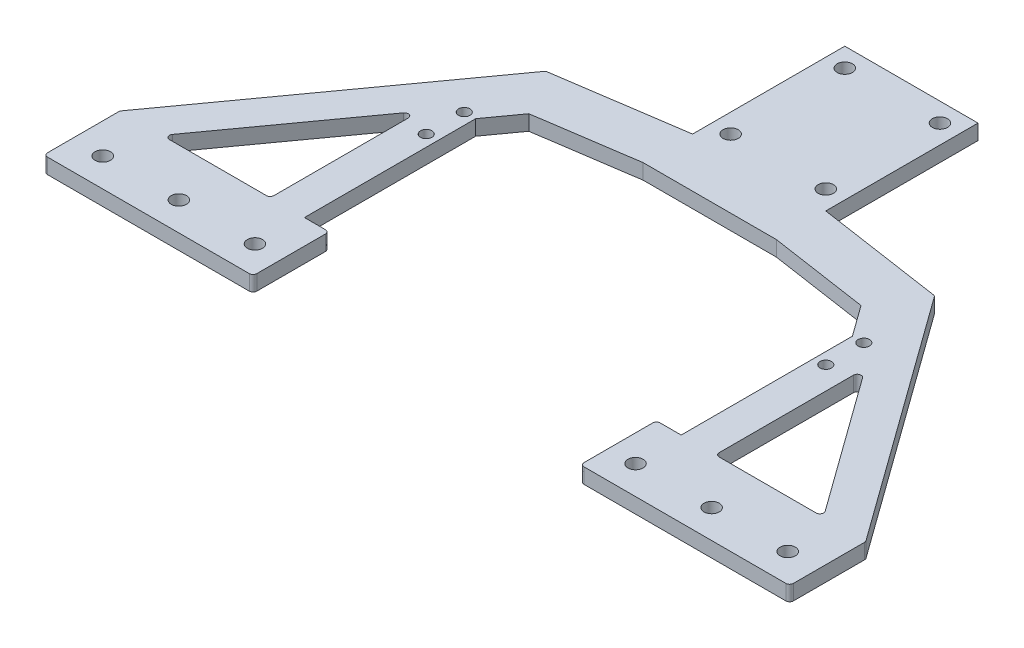
SolidWorks part; units mm, degrees
material "Thornel Mat VMA"
ref_plane "前视基准面" through (0, 0, 0) normal (0, 0, 1) x (1, 0, 0)
ref_plane "上视基准面" through (0, 0, 0) normal (0, 1, 0) x (1, 0, 0)
ref_plane "右视基准面" through (0, 0, 0) normal (1, 0, 0) x (0, 0, -1)
sketch "草图1" plane through (0, 0, 0) normal (0, 1, 0) x (1, 0, 0)
  line L0 (0, 0) -> (0, -110)
  line L1 (0, -110) -> (-62.5, -110)
  line L2 (-62.5, -110) -> (-62.5, -130)
  line L3 (-62.5, -130) -> (97.5, -130)
  line L4 (97.5, -130) -> (97.5, -110)
  line L5 (97.5, -110) -> (35, -110)
  line L6 (35, -110) -> (35, 0)
  line L7 (35, 0) -> (0, 0)
  line L9 (5, -5) -> (30, -5) construction
  line L10 (5, -5) -> (5, -35) construction
  line L11 (5, -35) -> (30, -35) construction
  line L12 (30, -5) -> (30, -35) construction
  circle A0 centre (5, -5) radius 2
  circle A1 centre (30, -5) radius 2
  circle A2 centre (5, -35) radius 2
  circle A3 centre (30, -35) radius 2
  circle A4 centre (-52.5, -122.5) radius 2
  circle A5 centre (-32.5, -122.5) radius 2
  circle A6 centre (-12.5, -122.5) radius 2
  circle A7 centre (7.5, -122.5) radius 2
  circle A8 centre (27.5, -122.5) radius 2
  circle A9 centre (47.5, -122.5) radius 2
  circle A10 centre (67.5, -122.5) radius 2
  circle A11 centre (87.5, -122.5) radius 2
  point P7 (17.5, -5)
  dimension "D10" = 4
  dimension "D11" = 7.5
  dimension "D13" = 4
  dimension "D1" = 35
  dimension "D2" = 130
  dimension "D3" = 20
  dimension "D4" = 160
  dimension "D5" = 62.5
  dimension "D6" = 5
  dimension "D7" = 5
  dimension "D8" = 5
  dimension "D9" = 30
  dimension "D12" = 10
  dimension "D15" = 10
  dimension "D14" = 8
extrude "凸台-拉伸1" add sketch "草图1" along normal blind 4
sketch "草图2" plane through (0, 4, 0) normal (0, 1, 0) x (1, 0, 0)
  line L0 (17.5, 0) -> (17.5, -130) construction
  line L1 (-35, -65) -> (70, -65) construction
  line L2 (-35, -65) -> (-35, -75) construction
  line L3 (-35, -75) -> (70, -75) construction
  line L5 (35, 0) -> (0, 0) construction
  line L6 (-62.5, -130) -> (97.5, -130) construction
  line L7 (70, -65) -> (70, -75) construction
  line L34 (0, 0) -> (0, -110) construction
  line L35 (0, -40) -> (0, -53)
  line L44 (0, -40) -> (-33.6, -45)
  line L45 (-33.6, -45) -> (-80.5, -110)
  line L46 (0, -53) -> (-26.1492, -56.8913)
  line L47 (-26.1492, -56.8913) -> (-32, -65)
  line L48 (-32, -65) -> (-32, -110)
  line L50 (-80.5, -110) -> (-80.5, -130)
  line L51 (-80.5, -130) -> (-62.5, -130)
  line L52 (-62.5, -130) -> (-62.5, -110)
  line L65 (0, -110) -> (-62.5, -110) construction
  line L66 (-32, -110) -> (-41, -110)
  line L67 (-69.4018, -110) -> (-41, -70.6372)
  line L68 (-41, -70.6372) -> (-41, -110)
  line L69 (-62.5, -110) -> (-69.4018, -110)
  line L71 (67, -65) -> (67, -110)
  line L72 (61.1492, -56.8913) -> (67, -65)
  line L73 (35, -53) -> (61.1492, -56.8913)
  line L74 (35, -40) -> (35, -53)
  line L75 (35, -40) -> (68.6, -45)
  line L76 (68.6, -45) -> (115.5, -110)
  line L77 (115.5, -110) -> (115.5, -130)
  line L78 (115.5, -130) -> (97.5, -130)
  line L79 (97.5, -130) -> (97.5, -110)
  line L80 (97.5, -110) -> (104.4018, -110)
  line L81 (104.4018, -110) -> (76, -70.6372)
  line L82 (76, -70.6372) -> (76, -110)
  line L83 (67, -110) -> (76, -110)
  line L84 (-52.5, -122.5) -> (-72.5, -122.5) construction
  circle A0 centre (-35, -65) radius 1.5
  circle A1 centre (-35, -75) radius 1.5
  circle A2 centre (70, -65) radius 1.5
  circle A3 centre (70, -75) radius 1.5
  circle A4 centre (-52.5, -122.5) radius 2 construction
  circle A5 centre (-72.5, -122.5) radius 2
  circle A6 centre (107.5, -122.5) radius 2
  dimension "D3" = 3
  dimension "D15" = 20
  dimension "D1" = 105
  dimension "D2" = 10
  dimension "D4" = 3
  dimension "D5" = 40
  dimension "D6" = 55
  dimension "D7" = 9
  dimension "D8" = 13
  dimension "D9" = 13
  dimension "D10" = 5
  dimension "D11" = 18
  dimension "D12" = 9
extrude "凸台-拉伸2" add sketch "草图2" against normal up to surface (4 mm away) up to face at (17.5, 0, 87.5)
sketch "草图3" plane through (0, 4, 0) normal (0, 1, 0) x (1, 0, 0)
  line L0 (0, -53) -> (35, -53)
  line L4 (35, -53) -> (35, -110)
  line L5 (35, -110) -> (60.5, -110)
  line L7 (60.5, -110) -> (60.5, -130)
  line L8 (-80.5, -130) -> (115.5, -130) construction
  line L9 (60.5, -130) -> (-25.5, -130)
  line L10 (-25.5, -130) -> (-25.5, -110)
  line L12 (-25.5, -110) -> (0, -110)
  line L13 (0, -110) -> (0, -53)
  line L15 (-80.5, -130) -> (115.5, -130) construction
  line L17 (0, -110) -> (-32, -110) construction
  line L18 (67, -110) -> (35, -110) construction
  circle A2 centre (-32.5, -122.5) radius 2 construction
  circle A3 centre (67.5, -122.5) radius 2 construction
  dimension "D1" = 7
  dimension "D2" = 7
extrude "切除-拉伸1" cut sketch "草图3" against normal through all
fillet "圆角2" radius 1 6 edges at (104.4018, 2, 110) (76, 2, 110) (76, 2, 70.6372) (-41, 2, 110) (-69.4018, 2, 110) (-41, 2, 70.6372)
fillet "圆角3" radius 1 10 edges at (-33.6, 2, 45) (68.6, 2, 45) (115.5, 2, 110) (115.5, 2, 130) (60.5, 2, 130) (60.5, 2, 110) (-80.5, 2, 110) (-80.5, 2, 130) (-25.5, 2, 130) (-25.5, 2, 110)
